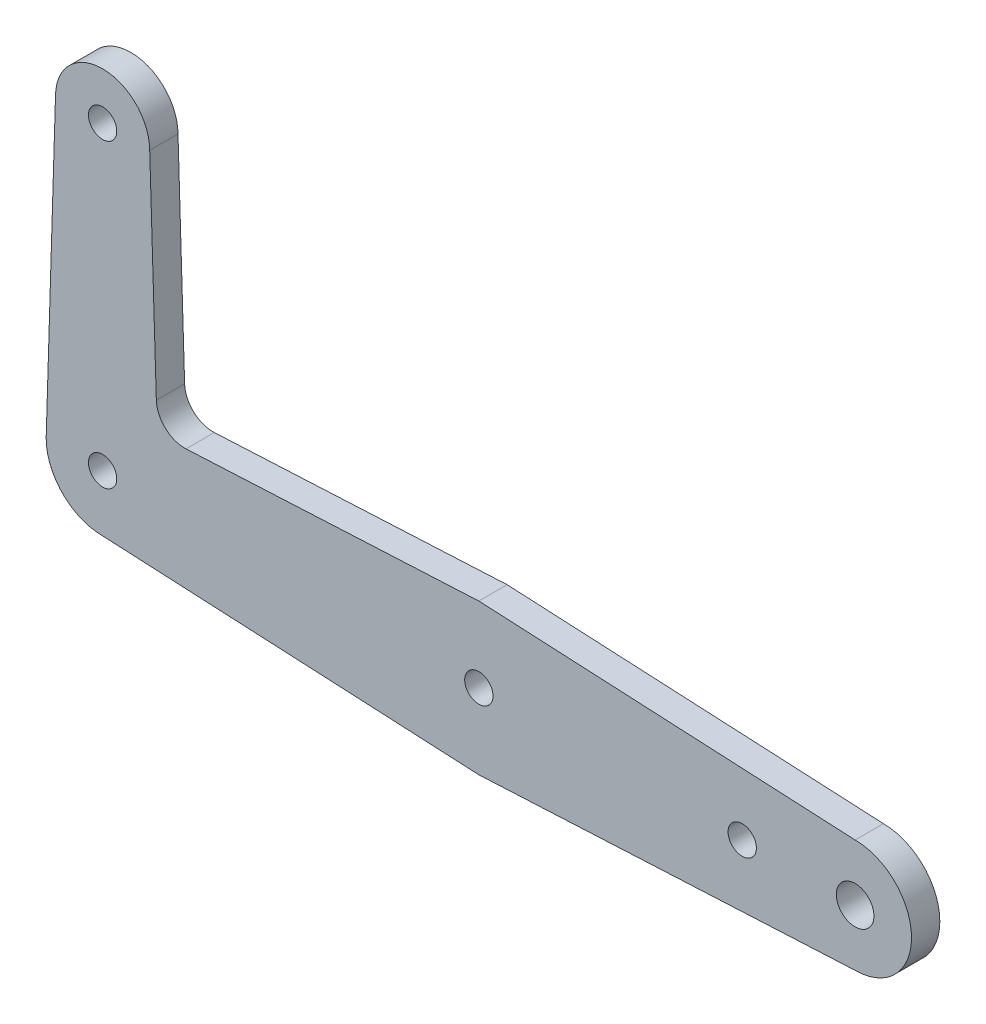
SolidWorks part; units mm, degrees
ref_plane "Front Plane" through (0, 0, 0) normal (0, 0, 1) x (1, 0, 0)
ref_plane "Top Plane" through (0, 0, 0) normal (0, 1, 0) x (1, 0, 0)
ref_plane "Right Plane" through (0, 0, 0) normal (1, 0, 0) x (0, 0, -1)
sketch "Sketch1" plane through (0, 0, 0) normal (0, 0, 1) x (1, 0, 0)
  line L0 (-7.9502, 0) -> (-9.525, -50.8)
  line L1 (7.9502, 0) -> (9.2154, -40.8142)
  line L2 (127, -41.275) -> (63.5, -38.1)
  line L3 (127, -60.325) -> (63.5, -63.5)
  line L4 (63.5, -38.1) -> (9.2154, -40.8142)
  line L5 (63.5, -63.5) -> (0, -60.325)
  line L6 (9.5067, -50.21) -> (9.525, -50.8)
  arc A0 (7.9502, 0) -> (-7.9502, 0) centre (0, 0) ccw
  arc A1 (-9.5067, -50.21) -> (0, -60.325) centre (0, -50.8) ccw
  arc A2 (62.2332, -63.4367) -> (64.7668, -63.4367) centre (63.5, -50.8) ccw
  arc A3 (127, -60.325) -> (127, -41.275) centre (127, -50.8) ccw
  arc A4 (9.525, -50.8) -> (9.5067, -50.21) centre (0, -50.8) ccw
  arc A5 (64.7668, -38.1633) -> (62.2332, -38.1633) centre (63.5, -50.8) ccw
  dimension "D1" = 15.9004
  dimension "D2" = 19.05
  dimension "D4" = 25.4
  dimension "D5" = 19.05
  dimension "D3" = 50.8
  dimension "D6" = 63.5
  dimension "D7" = 63.5
extrude "Boss-Extrude1" add sketch "Sketch1" along normal blind 4.7752 contours L3 A3 L2 L4 L1 A0 L0 A1 L5 A4 L6
fillet "Fillet1" radius 4.7752 1 edges at (9.2154, -40.8142, 2.3876)
sketch "Sketch2" plane through (0, 0, 4.7752) normal (0, 0, 1) x (1, 0, 0)
  circle A0 centre (0, 0) radius 2.3876
  circle A1 centre (0, -50.8) radius 2.3876
  circle A2 centre (63.5, -50.8) radius 2.3876
  circle A3 centre (107.95, -50.8) radius 2.3876
  dimension "D2" = 4.7752
  dimension "D3" = 4.7752
  dimension "D4" = 63.5
  dimension "D6" = 4.7752
  dimension "D7" = 4.7752
  dimension "D1" = 50.8
  dimension "D5" = 44.45
extrude "Cut-Extrude1" cut sketch "Sketch2" against normal through all
sketch "Sketch3" plane through (0, 0, 4.7752) normal (0, 0, 1) x (1, 0, 0)
  circle A0 centre (127, -50.8) radius 3.175
  dimension "D1" = 6.35
extrude "Cut-Extrude2" cut sketch "Sketch3" against normal blind 4.7752
